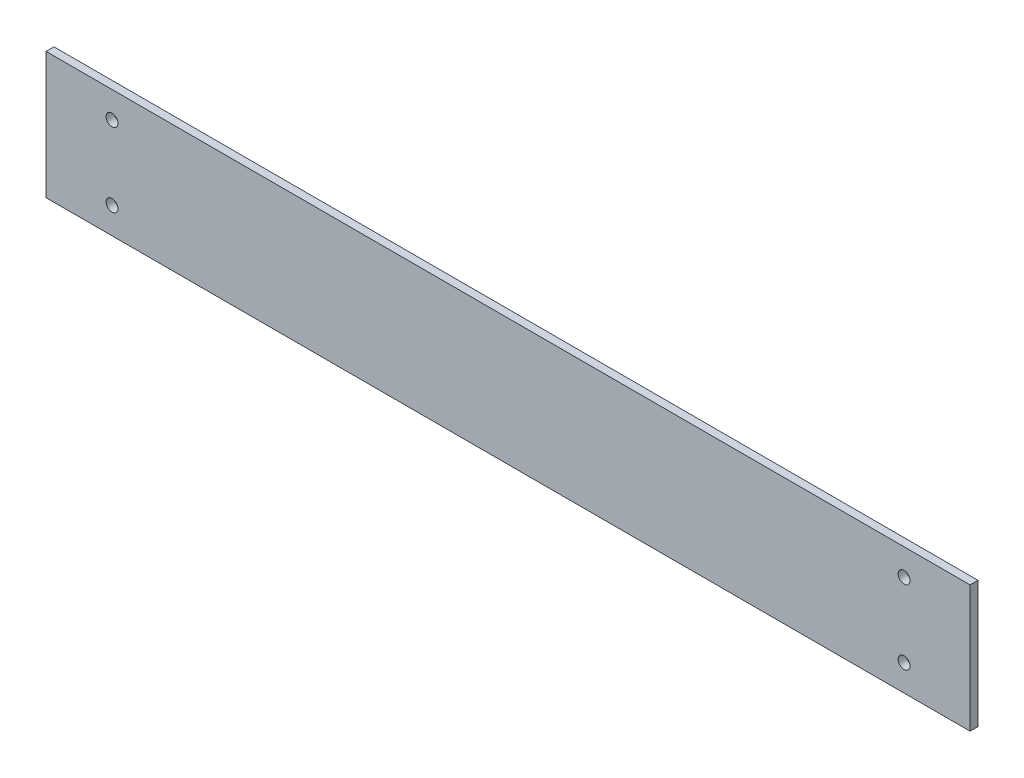
SolidWorks part; units mm, degrees
ref_plane "Plan de face" through (0, 0, 0) normal (0, 0, 1) x (1, 0, 0)
ref_plane "Plan de dessus" through (0, 0, 0) normal (0, 1, 0) x (1, 0, 0)
ref_plane "Plan de droite" through (0, 0, 0) normal (1, 0, 0) x (0, 0, -1)
sketch "Esquisse1" plane through (0, 0, 0) normal (0, 0, 1) x (1, 0, 0)
  line L0 (-175, 24) -> (175, -24) construction
  line L1 (-175, 24) -> (175, 24)
  line L2 (-175, 24) -> (-175, -24)
  line L3 (-175, -24) -> (175, -24)
  line L4 (175, 24) -> (175, -24)
  point P4 (0, 0)
  dimension "D1" = 350
  dimension "D2" = 48
extrude "Boss.-Extru.1" add sketch "Esquisse1" along normal blind 3
sketch "Esquisse2" plane through (0, 0, 3) normal (0, 0, 1) x (1, 0, 0)
  line L0 (-175, 14) -> (175, 14) construction
  line L1 (-175, 24) -> (-175, -24) construction
  line L2 (175, -24) -> (175, 24) construction
  line L3 (0, 14) -> (0, 24) construction
  line L4 (175, -14) -> (-175, -14) construction
  line L5 (175, 24) -> (-175, 24) construction
  line L6 (0, -14) -> (0, -24) construction
  line L7 (-175, -24) -> (175, -24) construction
  circle A0 centre (-150, 14) radius 2.25
  circle A1 centre (-150, -14) radius 2.25
  circle A2 centre (150, 14) radius 2.25
  circle A3 centre (150, -14) radius 2.25
  dimension "D2" = 4.5
  dimension "D3" = 25
  dimension "D1" = 10
extrude "Enlèv. mat.-Extru.1" cut sketch "Esquisse2" against normal up to next
